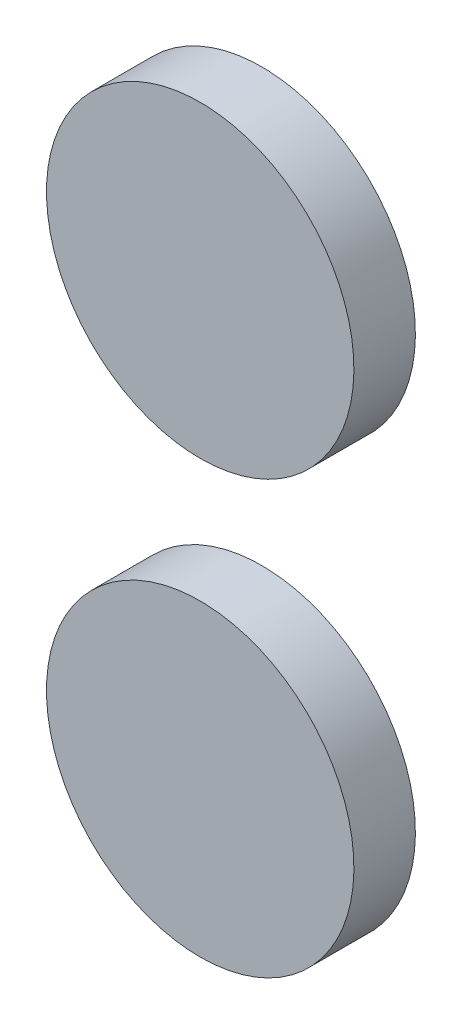
SolidWorks part; units mm, degrees
ref_plane "Plan de face" through (0, 0, 0) normal (0, 0, 1) x (1, 0, 0)
ref_plane "Plan de dessus" through (0, 0, 0) normal (0, 1, 0) x (1, 0, 0)
ref_plane "Plan de droite" through (0, 0, 0) normal (1, 0, 0) x (0, 0, -1)
sketch "Esquisse1" plane through (0, 0, 0) normal (0, 0, 1) x (1, 0, 0)
  ellipse E1 centre (5.4, 61.2666) end of major axis (5.4, 60.0123) minor radius 1.25
  ellipse E2 centre (5.4, 61.2666) end of major axis (5.4, 60.0123) minor radius 1.25
  ellipse E3 centre (5.4, 57.7545) end of major axis (5.4, 56.5001) minor radius 1.25
  ellipse E4 centre (5.4, 57.7545) end of major axis (5.4, 56.5001) minor radius 1.25
  dimension "D1" = 0
  dimension "D2" = 0
extrude "Boss.-Extru.1" add sketch "Esquisse1" along normal blind 0.5
